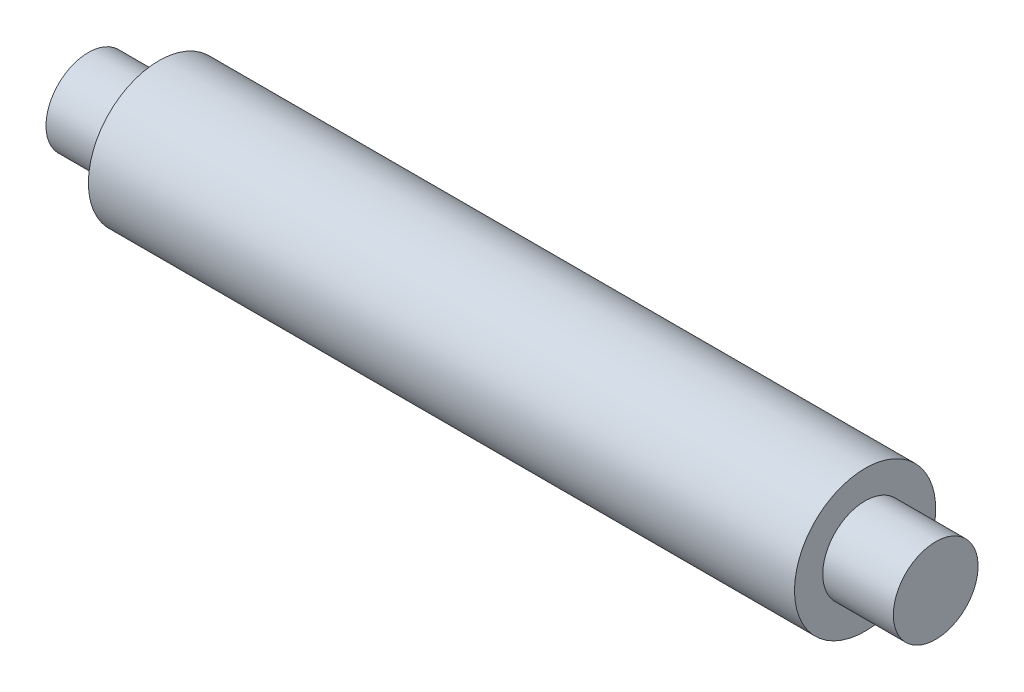
SolidWorks part; units mm, degrees
ref_plane "前基準面" through (0, 0, 0) normal (0, 0, 1) x (1, 0, 0)
ref_plane "上基準面" through (0, 0, 0) normal (0, 1, 0) x (1, 0, 0)
ref_plane "右基準面" through (0, 0, 0) normal (1, 0, 0) x (0, 0, -1)
sketch "草圖1" plane through (0, 0, 0) normal (0, 0, 1) x (1, 0, 0)
  line L1 (0, 0) -> (10, 0)
  line L2 (0, 0) -> (0, 6)
  line L3 (0, 6) -> (10, 6)
  line L4 (10, 0) -> (10, 6)
  line L5 (10, 0) -> (110, 0)
  line L6 (10, 0) -> (10, 10)
  line L7 (10, 10) -> (110, 10)
  line L8 (110, 0) -> (110, 10)
  line L9 (110, 0) -> (120, 0)
  line L10 (110, 0) -> (110, 6)
  line L11 (110, 6) -> (120, 6)
  line L12 (120, 0) -> (120, 6)
  dimension "D1" = 120
  dimension "D2" = 10
  dimension "D3" = 100
  dimension "D4" = 6
  dimension "D5" = 6
  dimension "D6" = 10
revolve "旋轉1" add sketch "草圖1" angle 360 about L1
